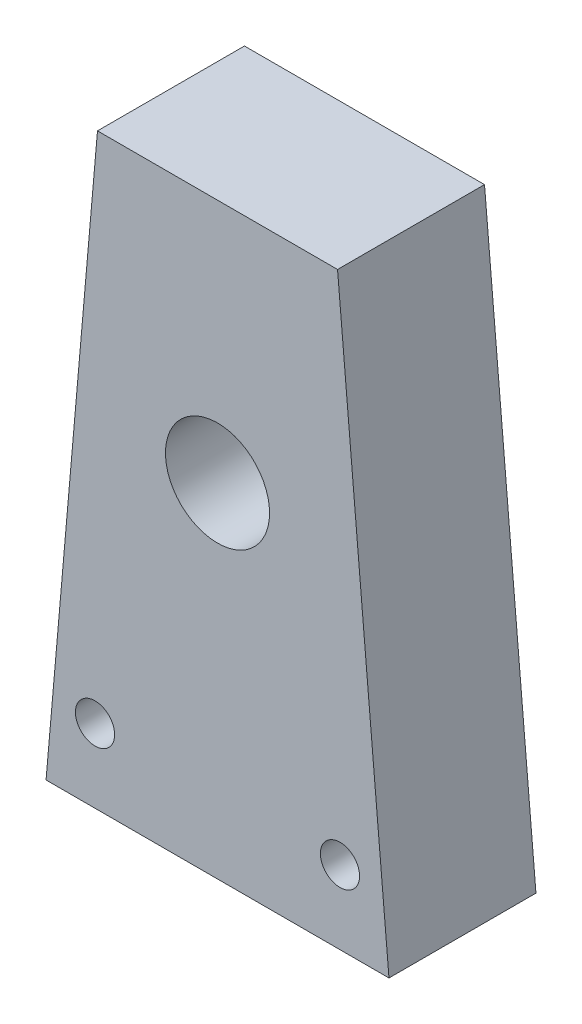
SolidWorks part; units mm, degrees
ref_plane "Front Plane" through (0, 0, 0) normal (0, 0, 1) x (1, 0, 0)
ref_plane "Top Plane" through (0, 0, 0) normal (0, 1, 0) x (1, 0, 0)
ref_plane "Right Plane" through (0, 0, 0) normal (1, 0, 0) x (0, 0, -1)
sketch "Sketch1" plane through (0, 0, 0) normal (0, 0, 1) x (1, 0, 0)
  line L0 (-14, 0) -> (14, 0)
  line L1 (14, 0) -> (9.8, 48)
  line L2 (9.8, 48) -> (-9.8, 48)
  line L3 (-9.8, 48) -> (-14, 0)
extrude "Boss-Extrude1" add sketch "Sketch1" along normal blind 12
sketch "Sketch2" plane through (0, 0, 0) normal (0, 0, 1) x (1, 0, 0)
  circle A0 centre (0, 28) radius 4.25
  circle A1 centre (10, 6) radius 1.6
  circle A2 centre (-10, 6) radius 1.6
extrude "Cut-Extrude2" cut sketch "Sketch2" along normal blind 13
